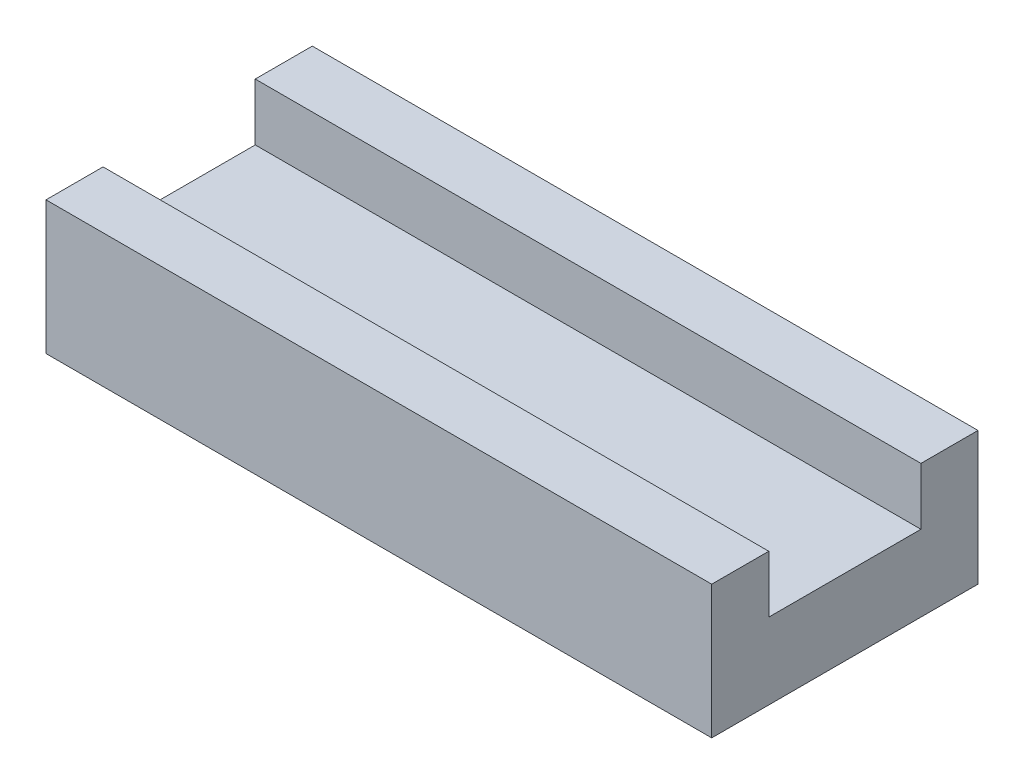
SolidWorks part; units mm, degrees
ref_plane "Front Plane" through (0, 0, 0) normal (0, 0, 1) x (1, 0, 0)
ref_plane "Top Plane" through (0, 0, 0) normal (0, 1, 0) x (1, 0, 0)
ref_plane "Right Plane" through (0, 0, 0) normal (1, 0, 0) x (0, 0, -1)
sketch "Sketch1" plane through (0, 0, 0) normal (1, 0, 0) x (0, 0, -1)
  line L0 (-7, 2) -> (-7, 5)
  line L1 (-7, -2) -> (7, -2)
  line L2 (-7, -2) -> (-7, 2)
  line L3 (-4, 2) -> (4, 2)
  line L4 (7, -2) -> (7, 2)
  line L5 (-7, -2) -> (7, 2) construction
  line L6 (-7, 2) -> (7, -2) construction
  line L7 (-7, 5) -> (-4, 5)
  line L8 (-4, 5) -> (-4, 2)
  line L9 (7, 2) -> (7, 5)
  line L10 (7, 5) -> (4, 5)
  line L11 (4, 5) -> (4, 2)
  point P0 (0, 0)
  point P12 (0, 2)
  point P13 (-4, 1.3048)
  point P14 (0, 0)
  point P15 (-7, 2.3631)
  dimension "D1" = 4
  dimension "D2" = 8
  dimension "D3" = 3
  dimension "D4" = 3
extrude "Boss-Extrude1" add sketch "Sketch1" against normal blind 35
